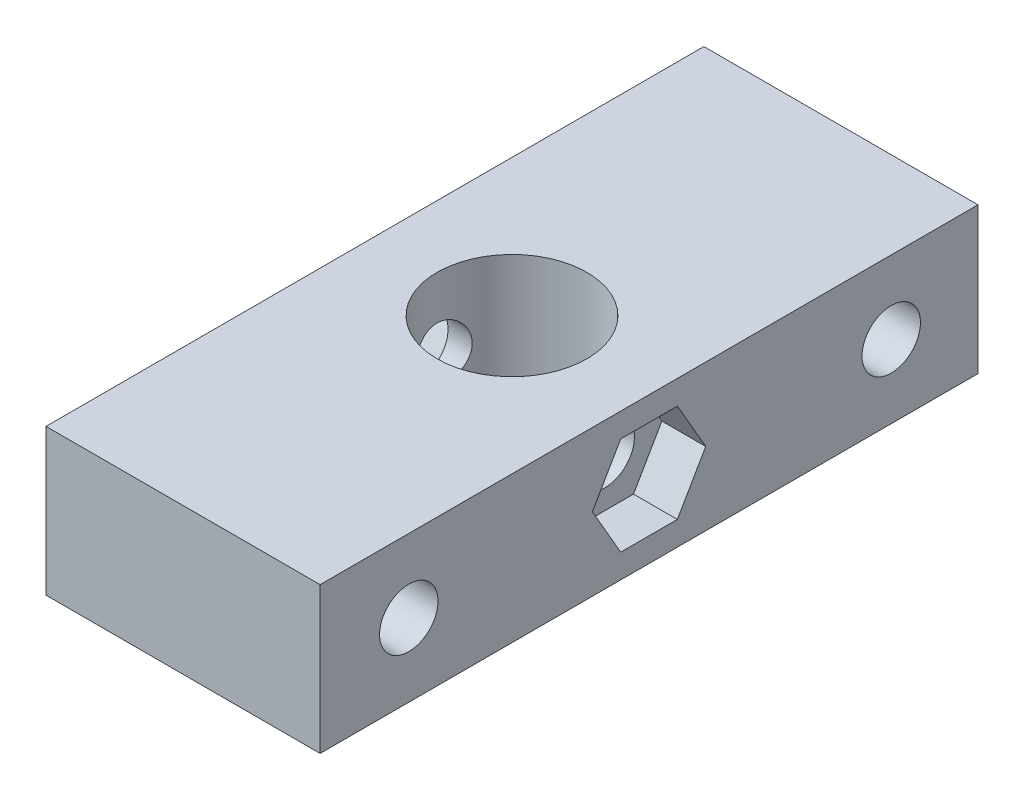
SolidWorks part; units mm, degrees
ref_plane "Front Plane" through (0, 0, 0) normal (0, 0, 1) x (1, 0, 0)
ref_plane "Top Plane" through (0, 0, 0) normal (0, 1, 0) x (1, 0, 0)
ref_plane "Right Plane" through (0, 0, 0) normal (1, 0, 0) x (0, 0, -1)
sketch "Sketch2" plane through (0, 0, 0) normal (0, 1, 0) x (1, 0, 0)
  line L1 (7.5, -18) -> (-7.5, -18)
  line L2 (7.5, -18) -> (7.5, 18)
  line L3 (7.5, 18) -> (-7.5, 18)
  line L4 (-7.5, -18) -> (-7.5, 18)
  line L5 (7.5, -18) -> (-7.5, 18) construction
  line L6 (7.5, 18) -> (-7.5, -18) construction
  point P0 (0, 0)
  dimension "D1" = 15
  dimension "D2" = 36
extrude "Boss-Extrude1" add sketch "Sketch2" along normal blind 8
sketch "Sketch4" plane through (0, 8, 0) normal (0, 1, 0) x (1, 0, 0)
  circle A0 centre (0, 0) radius 4.1
  dimension "D1" = 8.2
extrude "Cut-Extrude1" cut sketch "Sketch4" against normal through all
sketch "Sketch13" plane through (-7.5, 0, 0) normal (-1, 0, 0) x (0, 0, 1)
  line L0 (-18, 8) -> (18, 8) construction
  line L1 (16.3, 4) -> (14.75, 6.6847)
  line L2 (14.75, 6.6847) -> (11.65, 6.6847)
  line L3 (11.65, 6.6847) -> (10.1, 4)
  line L4 (10.1, 4) -> (11.65, 1.3153)
  line L5 (11.65, 1.3153) -> (14.75, 1.3153)
  line L6 (14.75, 1.3153) -> (16.3, 4)
  line L14 (-10.1, 4) -> (-11.65, 6.6847)
  line L15 (-11.65, 6.6847) -> (-14.75, 6.6847)
  line L16 (-14.75, 6.6847) -> (-16.3, 4)
  line L17 (-16.3, 4) -> (-14.75, 1.3153)
  line L18 (-14.75, 1.3153) -> (-11.65, 1.3153)
  line L19 (-11.65, 1.3153) -> (-10.1, 4)
  circle A0 centre (13.2, 4) radius 2.6847 construction
  circle A2 centre (-13.2, 4) radius 2.6847 construction
  dimension "D1" = 6.2
  dimension "D2" = 6.2
  dimension "D3" = 26.4
  dimension "D4" = 13.2
  dimension "D5" = 4
extrude "Cut-Extrude2" cut sketch "Sketch13" against normal blind 2.4
sketch "Sketch15" plane through (7.5, 0, 0) normal (1, 0, 0) x (0, 0, -1)
  line L1 (-3.1, 4) -> (-1.55, 1.3153)
  line L2 (-1.55, 1.3153) -> (1.55, 1.3153)
  line L3 (1.55, 1.3153) -> (3.1, 4)
  line L4 (3.1, 4) -> (1.55, 6.6847)
  line L5 (1.55, 6.6847) -> (-1.55, 6.6847)
  line L6 (-1.55, 6.6847) -> (-3.1, 4)
  circle A0 centre (0, 4) radius 2.6847 construction
  dimension "D1" = 6.2
  dimension "D2" = 4
extrude "Cut-Extrude5" cut sketch "Sketch15" against normal blind 2.4
sketch "Sketch16" plane through (5.1, 0, 0) normal (1, 0, 0) x (0, 0, -1)
  line L0 (-18, 0) -> (18, 0) construction
  circle A0 centre (0, 4) radius 1.6
  point P2 (0, 0)
  dimension "D1" = 4
sketch "Sketch20" plane through (-7.5, 0, 0) normal (-1, 0, 0) x (0, 0, 1)
  line L1 (3.1, 4) -> (1.55, 6.6847)
  line L2 (1.55, 6.6847) -> (-1.55, 6.6847)
  line L3 (-1.55, 6.6847) -> (-3.1, 4)
  line L4 (-3.1, 4) -> (-1.55, 1.3153)
  line L5 (-1.55, 1.3153) -> (1.55, 1.3153)
  line L6 (1.55, 1.3153) -> (3.1, 4)
  circle A0 centre (0, 4) radius 2.6847 construction
  dimension "D1" = 6.2
  dimension "D2" = 4
extrude "Cut-Extrude8" cut sketch "Sketch20" against normal blind 2.4
sketch "Sketch21" plane through (-5.1, 0, 0) normal (-1, 0, 0) x (0, 0, 1)
  circle A0 centre (0, 4) radius 1.6
  dimension "D1" = 3.2
extrude "Cut-Extrude9" cut sketch "Sketch21" against normal up to next
extrude "Cut-Extrude10" cut sketch "Sketch16" against normal up to next
sketch "Sketch24" plane through (-5.1, 0, 0) normal (-1, 0, 0) x (0, 0, 1)
  line L0 (-18, 0) -> (18, 0) construction
  circle A0 centre (13.147, 4) radius 1.6
  circle A1 centre (-13.253, 4) radius 1.6
  dimension "D1" = 26.4
  dimension "D2" = 4
extrude "Cut-Extrude11" cut sketch "Sketch24" against normal through all
